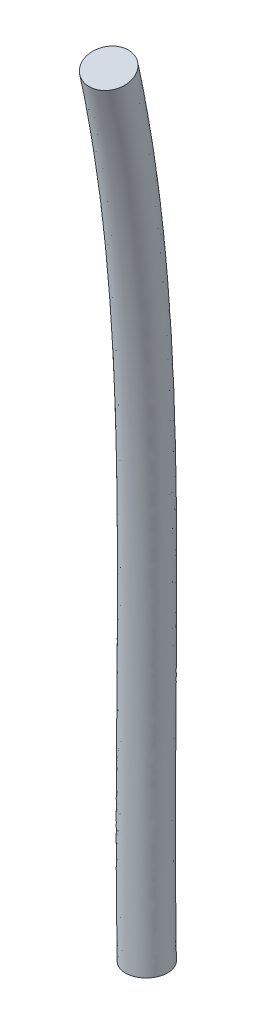
SolidWorks part; units mm, degrees
material "Custom Plastic"
ref_plane "X-Y Datum" through (0, 0, 0) normal (0, 0, 1) x (1, 0, 0)
ref_plane "X-Z Datum" through (0, 0, 0) normal (0, 1, 0) x (1, 0, 0)
ref_plane "Y-Z Datum" through (0, 0, 0) normal (1, 0, 0) x (0, 0, -1)
sketch3d "3DSketch1"
  line L0 (-26.9885, -164.006, 228.5635) -> (-26.9885, -140.506, 228.5635) construction
  circle A2 centre (-22.9865, -45.7731, 238.2462) radius 2.286 construction
  spline S0 degree 3 poles (-22.9865, -45.7731, 238.2462) (-25.3579, -86.5791, 227.4263) (-27.7095, -128.1411, 228.6099) (-26.8979, -169.6, 228.5635) knots 0 0 0 0 1 1 1 1
  point P2 (-26.8979, -169.6, 228.5635)
  point P10 (-22.9865, -48.0591, 238.2462)
sweep "Sweep1" add path "3DSketch1" circular profile diameter 6.35 parameters "D3"=6.35
